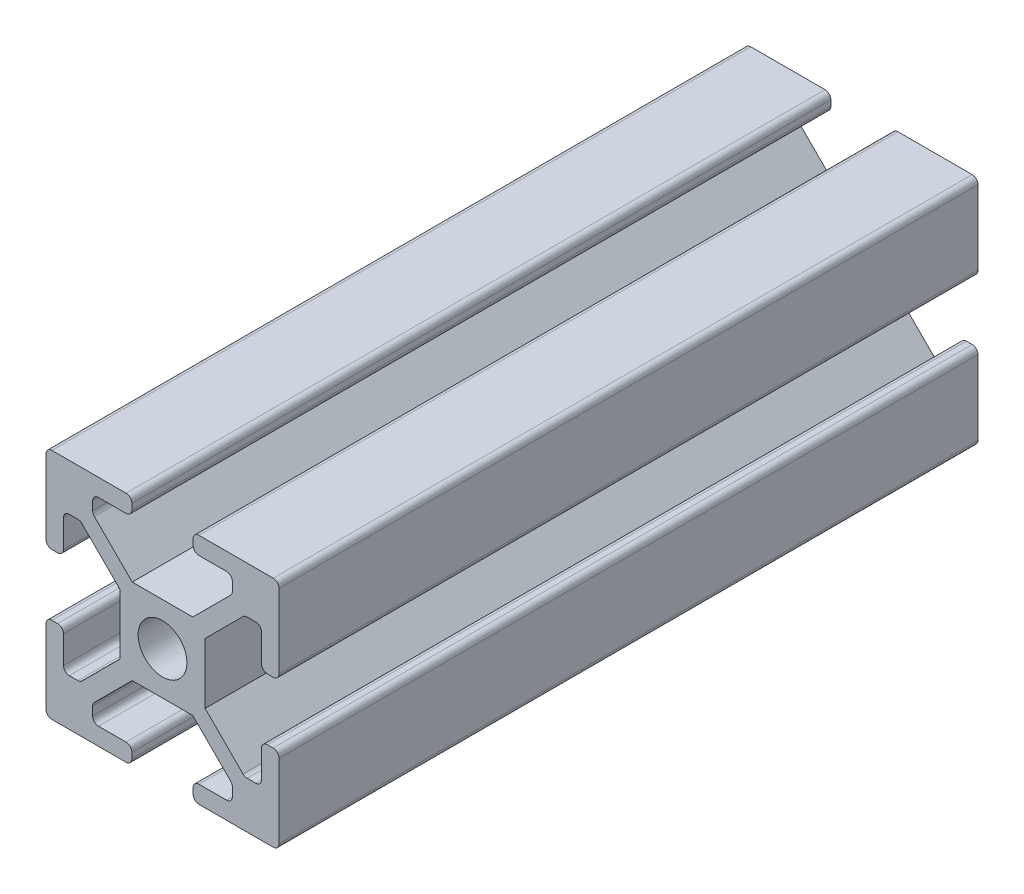
SolidWorks part; units mm, degrees
ref_plane "Front Plane" through (0, 0, 0) normal (0, 0, 1) x (1, 0, 0)
ref_plane "Top Plane" through (0, 0, 0) normal (0, 1, 0) x (1, 0, 0)
ref_plane "Right Plane" through (0, 0, 0) normal (1, 0, 0) x (0, 0, -1)
sketch "Sketch2" plane through (0, 0, 0) normal (0, 0, 1) x (1, 0, 0)
  line L0 (0, 3.66) -> (2.5993, 3.66)
  line L1 (0, 0) -> (3.66, 0)
  line L2 (0, 0) -> (0, 3.66)
  line L3 (2.63, 10) -> (10, 10)
  line L4 (10, 2.63) -> (10, 10)
  line L5 (3.66, 2.5993) -> (3.66, 0)
  line L6 (3.66, 3.66) -> (10, 10) construction
  line L7 (2.5993, 3.66) -> (5.995, 7.0557)
  line L8 (5.995, 7.0557) -> (5.995, 8.5)
  line L9 (5.995, 8.5) -> (2.63, 8.5)
  line L10 (2.63, 8.5) -> (2.63, 10)
  line L11 (3.66, 2.5993) -> (7.0557, 5.995)
  line L12 (7.0557, 5.995) -> (8.5, 5.995)
  line L13 (8.5, 5.995) -> (8.5, 2.63)
  line L14 (8.5, 2.63) -> (10, 2.63)
  line L15 (5.995, 7.0557) -> (6.5253, 6.5253) construction
  line L16 (6.5253, 6.5253) -> (7.0557, 5.995) construction
  line L17 (0, 3.66) -> (0, 10) construction
  line L18 (3.66, 0) -> (10, 0) construction
  line L19 (0, 10) -> (2.63, 10) construction
  line L20 (10, 0) -> (10, 2.63) construction
  line L21 (2.5993, 3.66) -> (3.66, 3.66) construction
  line L22 (3.66, 3.66) -> (3.66, 2.5993) construction
  dimension "D1" = 10
  dimension "D2" = 3.66
  dimension "D3" = 1.5
  dimension "D4" = 2.63
  dimension "D5" = 1.5
  dimension "D6" = 5.995
extrude "Boss-Extrude1" add sketch "Sketch2" along normal mid plane 60
fillet "Fillet1" radius 0.5 9 edges at (7.0557, 5.995, 0) (5.995, 7.0557, 0) (5.995, 8.5, 0) (8.5, 5.995, 0) (2.63, 8.5, 0) (2.63, 10, 0) (8.5, 2.63, 0) (10, 2.63, 0) (10, 10, 0)
pattern_circular "CirPattern3" count 4 over 360 about axis through (0, 0, 30) along (0, 0, -1) of "Fillet1", "Boss-Extrude1"
sketch "Sketch3" plane through (0, 0, 30) normal (0, 0, 1) x (1, 0, 0)
  circle A0 centre (0, 0) radius 2.095
  dimension "D1" = 4.19
extrude "Cut-Extrude1" cut sketch "Sketch3" against normal through all
